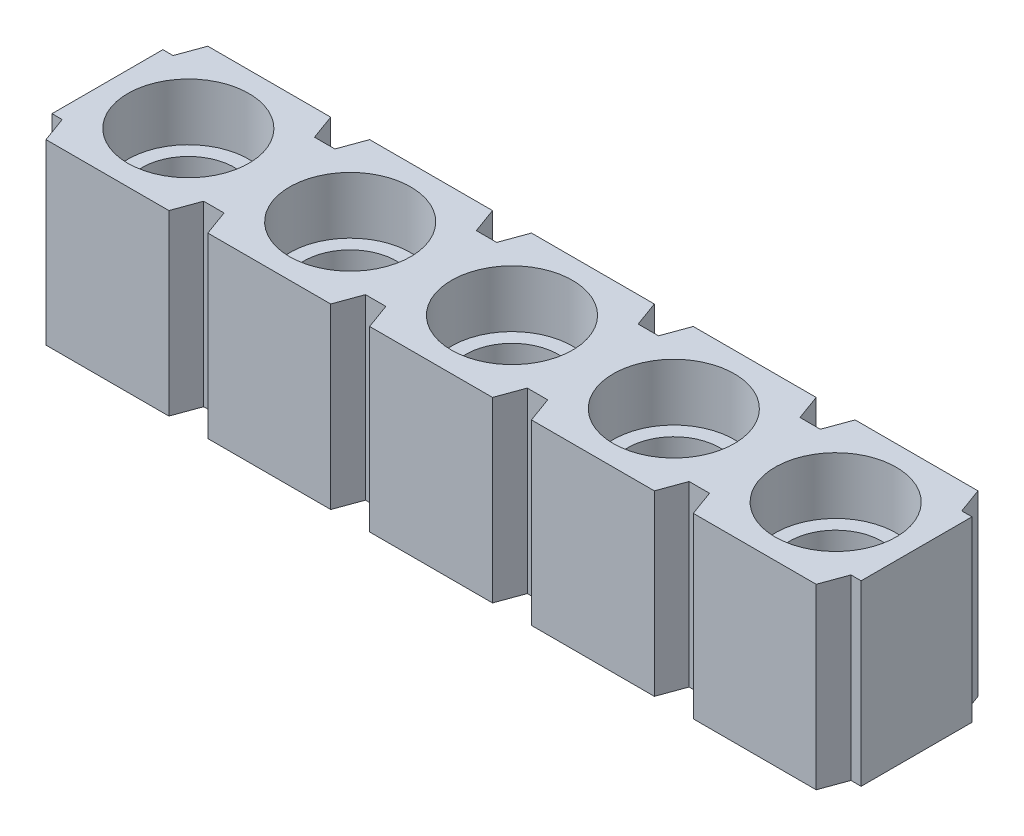
SolidWorks part; units mm, degrees
material "PCT Polyester"
ref_plane "Front Plane" through (0, 0, 0) normal (0, 0, 1) x (1, 0, 0)
ref_plane "Top Plane" through (0, 0, 0) normal (0, 1, 0) x (1, 0, 0)
ref_plane "Right Plane" through (0, 0, 0) normal (1, 0, 0) x (0, 0, -1)
sketch "Sketch1" plane through (0, 0, 0) normal (0, 1, 0) x (1, 0, 0)
  line L0 (12.3944, 0.4) -> (12.2344, 0.4)
  line L1 (12.3944, 2.1399) -> (12.3944, 0.4)
  line L2 (-0.3056, 2.1399) -> (-0.1456, 2.1399)
  line L3 (-0.3056, 2.1399) -> (-0.3056, 0.4)
  line L4 (0, 0) -> (12.0887, 0)
  line L5 (0, 2.54) -> (-0.1456, 2.1399)
  line L6 (0, 0) -> (-0.1456, 0.4)
  line L7 (-0.3056, 0.4) -> (-0.1456, 0.4)
  line L9 (12.0887, 0) -> (12.2344, 0.4)
  line L10 (12.0887, 2.54) -> (12.2344, 2.1399)
  line L11 (12.3944, 2.1399) -> (12.2344, 2.1399)
  line L16 (12.0887, 2.54) -> (0, 2.54)
  dimension "D2" = 2.54
  dimension "D3" = 20
  dimension "D4" = 0.4
  dimension "D5" = 0.4
  dimension "D7" = 0.16
  dimension "INSLENGTH" = 12.7
extrude "Extrude1" add sketch "Sketch1" against normal blind 2.794
hole_wizard "Hole1" positions "3DSketch2" profile "Sketch3" legacy end condition through all
sketch3d "3DSketch2"
  line L2 (-0.3056, 0, -2.1399) -> (-0.3056, 0, -0.4) construction
  line L3 (12.0887, 0, -2.54) -> (0, 0, -2.54) construction
  point P0 (0.9644, 0, -1.27)
  dimension "D1" = 1.27
  dimension "D2" = 1.27
sketch "Sketch3" plane through (0.9644, 0, -1.27) normal (1, 0, 0) x (0, 0, 1)
  line L0 (0, 0) -> (0, 2.794)
  line L1 (0, 2.794) -> (0.7252, 2.794)
  line L2 (0.7252, 2.794) -> (0.7252, 0.8941)
  line L3 (0.7252, 0.8941) -> (0.95, 0.8941)
  line L4 (0.95, 0.8941) -> (0.95, 0)
  line L5 (0.95, 0) -> (0, 0)
  line L6 (0, 110) -> (0, -10) construction
  dimension "Diameter" = 1.4503
  dimension "Depth" = 2.794
  dimension "C-Bore Diameter" = 1.8999
  dimension "C-Bore Depth" = 0.8941
sketch "Sketch4" plane through (0, 0, 0) normal (0, 1, 0) x (1, 0, 0)
  line L0 (1.9288, 0) -> (2.54, 0)
  line L2 (0, 0) -> (12.0887, 0) construction
  line L5 (2.0744, 0.4) -> (1.9288, 0)
  line L6 (2.3944, 0.4) -> (2.54, 0)
  line L7 (12.0887, 2.54) -> (0, 2.54) construction
  line L8 (2.0744, 0.4) -> (2.3944, 0.4)
  line L10 (2.0744, 2.1399) -> (2.3944, 2.1399)
  line L11 (2.3944, 2.1399) -> (2.54, 2.54)
  line L12 (2.0744, 2.1399) -> (1.9288, 2.54)
  line L13 (1.9288, 2.54) -> (2.54, 2.54)
  line L17 (-0.3056, 2.1399) -> (-0.3056, 0.4) construction
  dimension "D1" = 0.4
  dimension "D2" = 0.32
  dimension "D3" = 70
  dimension "D4" = 0.6112
  dimension "D5" = 0.4001
  dimension "D6" = 2.2344
extrude "Extrude2" cut sketch "Sketch4" against normal blind 2.794
pattern_linear "LPattern1" count 5 spacing 2.54 along (1, 0, 0) of "Hole1"
pattern_linear "LPattern2" count 63 spacing 2.54 along (1, 0, 0) of "Extrude2"
